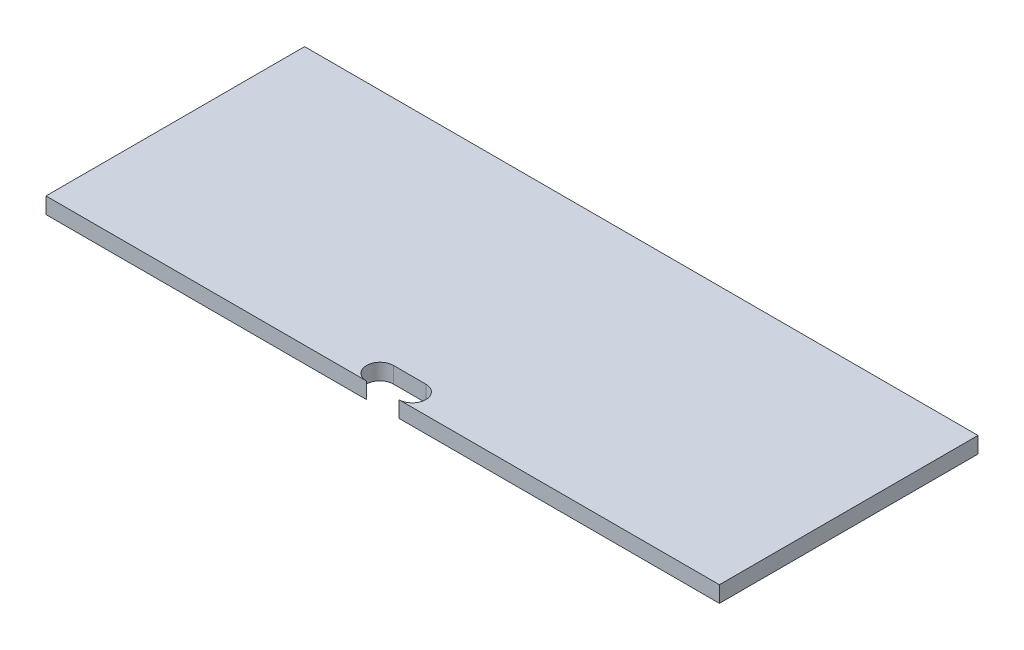
SolidWorks part; units mm, degrees
ref_plane "Front Plane" through (0, 0, 0) normal (0, 0, 1) x (1, 0, 0)
ref_plane "Top Plane" through (0, 0, 0) normal (0, 1, 0) x (1, 0, 0)
ref_plane "Right Plane" through (0, 0, 0) normal (1, 0, 0) x (0, 0, -1)
sketch "Sketch1" plane through (0, 0, 0) normal (0, 1, 0) x (1, 0, 0)
  line L1 (-62.5, -24) -> (62.5, -24)
  line L2 (-62.5, -24) -> (-62.5, 24)
  line L3 (-62.5, 24) -> (62.5, 24)
  line L4 (62.5, -24) -> (62.5, 24)
  line L5 (-62.5, -24) -> (62.5, 24) construction
  line L6 (-62.5, 24) -> (62.5, -24) construction
  point P0 (0, 0)
  dimension "D1" = 125
  dimension "D2" = 48
extrude "Boss-Extrude1" add sketch "Sketch1" along normal blind 3
sketch "Sketch2" plane through (0, 3, 0) normal (0, 1, 0) x (1, 0, 0)
  line L0 (0, 0) -> (0, -24) construction
  line L1 (-62.5, -24) -> (62.5, -24) construction
  line L2 (0, -19) -> (3, -19)
  line L3 (3, -24) -> (-3, -24)
  line L5 (0, -19) -> (-3, -19)
  arc A0 (-3, -19) -> (-3, -24) centre (-3, -21.5) ccw
  arc A1 (3, -19) -> (3, -24) centre (3, -21.5) cw
  point P9 (-1.5, -19)
  point P10 (0, 0)
  point P11 (0, 0)
  point P15 (-5.5, -21.5)
  dimension "D1" = 2.5
  dimension "D3" = 5
  dimension "D2" = 5.5
extrude "Cut-Extrude1" cut sketch "Sketch2" against normal blind 3
